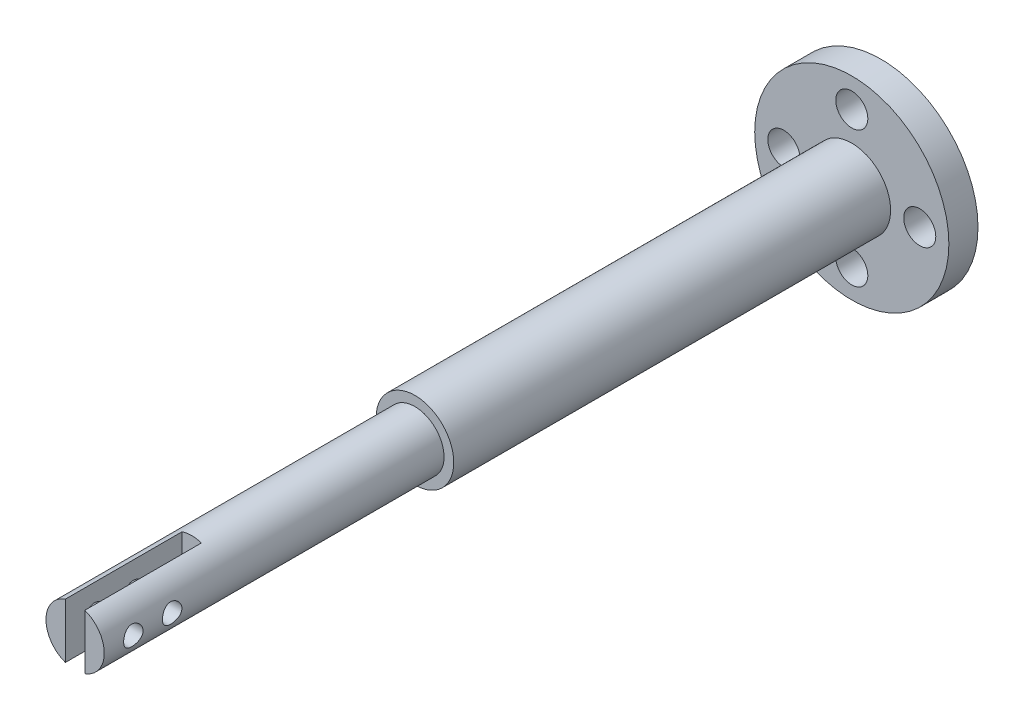
SolidWorks part; units mm, degrees
ref_plane "前视基准面" through (0, 0, 0) normal (0, 0, 1) x (1, 0, 0)
ref_plane "上视基准面" through (0, 0, 0) normal (0, 1, 0) x (1, 0, 0)
ref_plane "右视基准面" through (0, 0, 0) normal (1, 0, 0) x (0, 0, -1)
sketch "草图1" plane through (0, 0, 0) normal (0, 0, 1) x (1, 0, 0)
  line L0 (-10, 0) -> (10, 0) construction
  line L1 (0, 10) -> (0, -10.2805) construction
  circle A0 centre (0, 0) radius 10
  circle A1 centre (0, 7) radius 1.65
  circle A2 centre (7, 0) radius 1.65
  circle A3 centre (0, -7) radius 1.65
  circle A4 centre (-7, 0) radius 1.65
  dimension "D1" = 20
  dimension "D2" = 3.3
  dimension "D3" = 3.3
  dimension "D4" = 3.3
  dimension "D5" = 3.3
  dimension "D6" = 7
  dimension "D7" = 7
  dimension "D8" = 7
  dimension "D9" = 7
extrude "凸台-拉伸1" add sketch "草图1" along normal blind 3
sketch "草图2" plane through (0, 0, 3) normal (0, 0, 1) x (1, 0, 0)
  circle A0 centre (0, 0) radius 3
  dimension "D1" = 6
extrude "凸台-拉伸2" add sketch "草图2" along normal blind 80
sketch "草图3" plane through (0, 0, 83) normal (0, 0, 1) x (1, 0, 0)
  line L1 (-1, -3.8717) -> (1, -3.8717)
  line L2 (-1, -3.8717) -> (-1, 3.8717)
  line L3 (-1, 3.8717) -> (1, 3.8717)
  line L4 (1, -3.8717) -> (1, 3.8717)
  line L5 (-1, -3.8717) -> (1, 3.8717) construction
  line L6 (-1, 3.8717) -> (1, -3.8717) construction
  point P0 (0, 0)
  dimension "D1" = 7.7434
  dimension "D2" = 2
extrude "切除-拉伸1" cut sketch "草图3" against normal blind 12
sketch "草图5" plane through (-1, 0, 0) normal (1, 0, 0) x (0, 0, -1)
  line L0 (-83, 2.8284) -> (-83, -2.8284) construction
  line L1 (-83, 0) -> (-71.6344, 0) construction
  circle A0 centre (-80, 0) radius 1
  circle A1 centre (-76, 0) radius 1
  dimension "D1" = 2
  dimension "D2" = 2
  dimension "D3" = 3
  dimension "D4" = 4
extrude "切除-拉伸2" cut sketch "草图5" against normal mid plane 10
sketch "草图6" plane through (0, 0, 3) normal (0, 0, 1) x (1, 0, 0)
  circle A0 centre (0, 0) radius 4
  dimension "D1" = 8
extrude "凸台-拉伸3" add sketch "草图6" along normal blind 45
